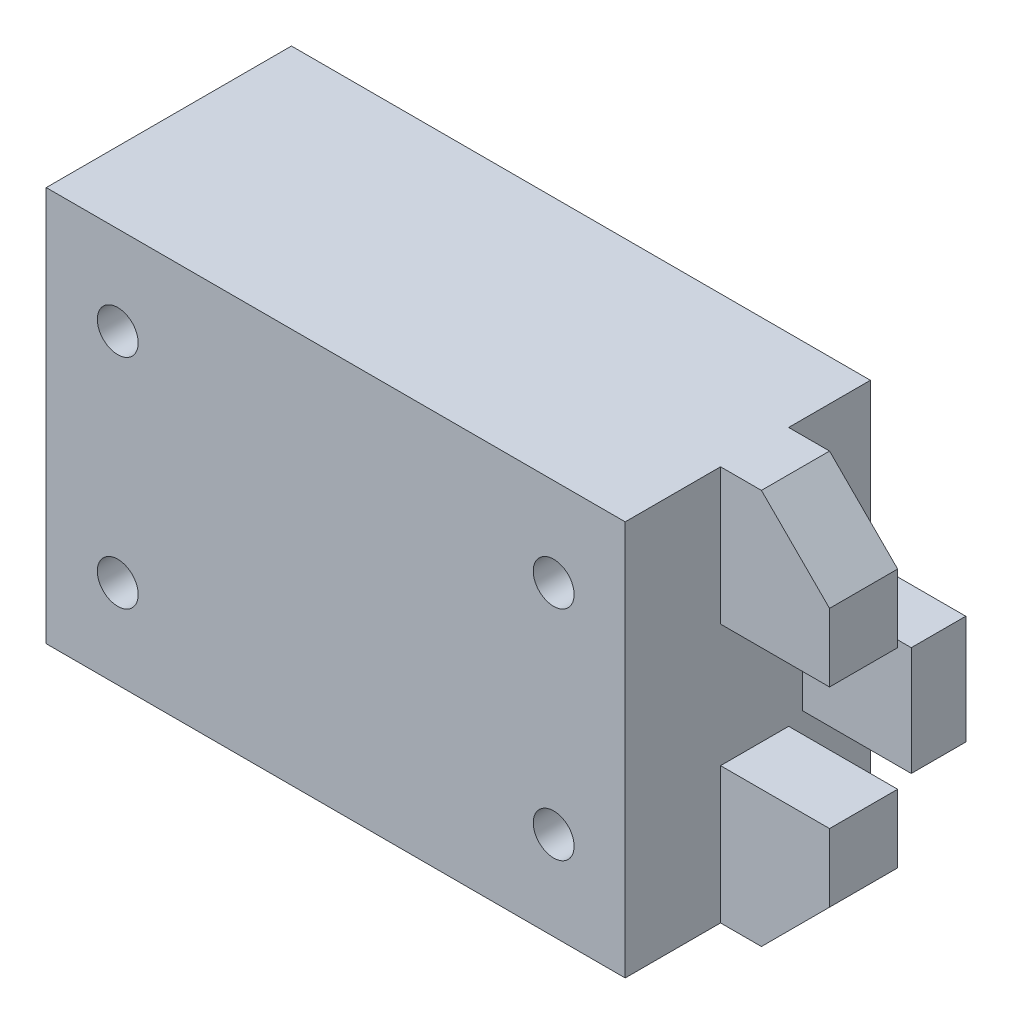
SolidWorks part; units mm, degrees
ref_plane "前视基准面" through (0, 0, 0) normal (0, 0, 1) x (1, 0, 0)
ref_plane "上视基准面" through (0, 0, 0) normal (0, 1, 0) x (1, 0, 0)
ref_plane "右视基准面" through (0, 0, 0) normal (1, 0, 0) x (0, 0, -1)
sketch "草图1" plane through (0, 0, 0) normal (0, 0, 1) x (1, 0, 0)
  line L0 (0, 29) -> (85, 29) construction
  line L1 (0, 0) -> (85, 0)
  line L2 (0, 0) -> (0, 58)
  line L3 (0, 58) -> (85, 58)
  line L4 (85, 0) -> (85, 58)
  line L6 (10.5, 13) -> (74.5, 13) construction
  line L7 (10.5, 13) -> (10.5, 45) construction
  line L8 (10.5, 45) -> (74.5, 45) construction
  line L9 (74.5, 13) -> (74.5, 45) construction
  line L10 (10.5, 13) -> (74.5, 45) construction
  line L11 (10.5, 45) -> (74.5, 13) construction
  circle A0 centre (10.5, 45) radius 1.75
  circle A1 centre (74.5, 45) radius 1.75
  circle A2 centre (10.5, 13) radius 1.75
  circle A3 centre (74.5, 13) radius 1.75
  point P7 (42.5, 29)
  dimension "D5" = 3.5
  dimension "D1" = 85
  dimension "D2" = 58
  dimension "D3" = 64
  dimension "D4" = 32
extrude "凸台-拉伸1" add sketch "草图1" along normal blind 36
sketch "草图2" plane through (0, 0, 36) normal (0, 0, 1) x (1, 0, 0)
  circle A0 centre (10.5, 45) radius 3
  circle A1 centre (74.5, 45) radius 3
  circle A2 centre (74.5, 13) radius 3
  circle A3 centre (10.5, 13) radius 3
  dimension "D1" = 6
extrude "切除-拉伸1" cut sketch "草图2" against normal offset from surface (31 mm away) 5 up to face at (12.25, 13, 0)
sketch "草图5" plane through (85, 0, 0) normal (1, 0, 0) x (0, 0, -1)
  line L0 (0, 0) -> (0, 58) construction
  line L1 (-2, 21) -> (-10, 21)
  line L2 (-2, 21) -> (-2, 37)
  line L3 (-2, 37) -> (-10, 37)
  line L4 (-10, 21) -> (-10, 37)
  line L5 (-2, 29) -> (0, 29) construction
  dimension "D1" = 2
  dimension "D2" = 10
  dimension "D3" = 16
extrude "电源线" add sketch "草图5" along normal blind 16
sketch "草图6" plane through (85, 0, 0) normal (1, 0, 0) x (0, 0, -1)
  line L0 (-36, 58) -> (0, 58) construction
  line L1 (-12, 58) -> (-22, 58)
  line L2 (-12, 58) -> (-12, 38)
  line L3 (-12, 38) -> (-22, 38)
  line L4 (-22, 58) -> (-22, 38)
  line L5 (-36, 0) -> (0, 0) construction
  line L6 (-12, 0) -> (-22, 0)
  line L7 (-12, 0) -> (-12, 20)
  line L8 (-12, 20) -> (-22, 20)
  line L9 (-22, 0) -> (-22, 20)
  line L10 (0, 0) -> (0, 58) construction
  dimension "D1" = 10
  dimension "D2" = 12
  dimension "D3" = 20
extrude "凸台-拉伸2" add sketch "草图6" along normal blind 16
chamfer "倒角1" distance 10 angle 45 2 edges at (101, 58, 17) (101, 0, 17)
